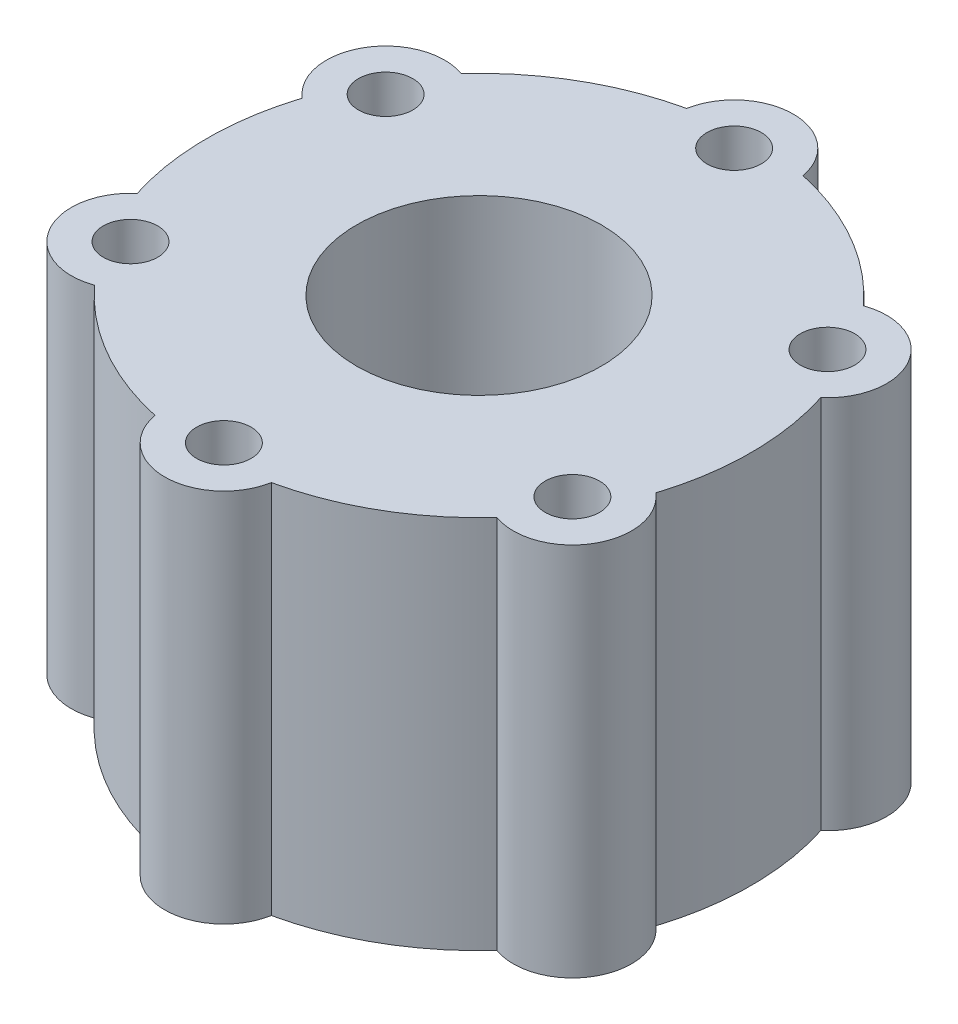
SolidWorks part; units mm, degrees
ref_plane "Front Plane" through (0, 0, 0) normal (0, 0, 1) x (1, 0, 0)
ref_plane "Top Plane" through (0, 0, 0) normal (0, 1, 0) x (1, 0, 0)
ref_plane "Right Plane" through (0, 0, 0) normal (1, 0, 0) x (0, 0, -1)
sketch "Sketch1" plane through (0, 0, 0) normal (0, 1, 0) x (1, 0, 0)
  line L0 (0, 0) -> (0, 23.8125) construction
  line L1 (0, 0) -> (20.6222, 11.9063) construction
  arc A0 (-5.4333, 24.8121) -> (-18.7712, 17.1114) centre (0, 0) ccw
  circle A1 centre (0, 23.8125) radius 2.54
  circle A2 centre (0, 0) radius 29.337 construction
  arc A3 (5.4333, 24.8121) -> (-5.4333, 24.8121) centre (0, 23.8125) ccw
  circle A4 centre (20.6222, 11.9063) radius 2.54
  arc A5 (24.2045, 7.7006) -> (18.7712, 17.1114) centre (20.6222, 11.9063) ccw
  circle A6 centre (20.6222, -11.9062) radius 2.54
  arc A7 (18.7712, -17.1114) -> (24.2045, -7.7006) centre (20.6222, -11.9062) ccw
  circle A8 centre (0, -23.8125) radius 2.54
  arc A9 (-5.4333, -24.8121) -> (5.4333, -24.8121) centre (0, -23.8125) ccw
  circle A10 centre (-20.6222, -11.9063) radius 2.54
  arc A11 (-24.2045, -7.7006) -> (-18.7712, -17.1114) centre (-20.6222, -11.9063) ccw
  circle A12 centre (-20.6222, 11.9062) radius 2.54
  arc A13 (-18.7712, 17.1114) -> (-24.2045, 7.7006) centre (-20.6222, 11.9062) ccw
  arc A14 (-24.2045, 7.7006) -> (-24.2045, -7.7006) centre (0, 0) ccw
  arc A15 (-18.7712, -17.1114) -> (-5.4333, -24.8121) centre (0, 0) ccw
  arc A16 (5.4333, -24.8121) -> (18.7712, -17.1114) centre (0, 0) ccw
  circle A17 centre (0, 0) radius 15.875
  arc A18 (24.2045, -7.7006) -> (24.2045, 7.7006) centre (0, 0) ccw
  arc A19 (18.7712, 17.1114) -> (5.4333, 24.8121) centre (0, 0) ccw
  point P29 (0, 0)
  dimension "D1" = 50.8
  dimension "D2" = 5.08
  dimension "D4" = 58.674
  dimension "D5" = 31.75
  dimension "D3" = 23.8125
  dimension "D6" = 60
extrude "Boss-Extrude1" add sketch "Sketch1" along normal blind 4.699
ref_plane "Plane1" through (0, 35, 0) normal (0, -1, 0) x (-1, 0, 0)
sketch "Sketch2" plane through (0, 4.699, 0) normal (0, 1, 0) x (1, 0, 0)
  circle A0 centre (0, 0) radius 11.426
  circle A1 centre (20.6222, -11.9062) radius 2.54
  circle A2 centre (20.6222, -11.9062) radius 2.54
  circle A3 centre (20.6222, 11.9063) radius 2.54
  circle A4 centre (20.6222, 11.9063) radius 2.54
  circle A5 centre (0, 23.8125) radius 2.54
  circle A6 centre (0, 23.8125) radius 2.54
  circle A7 centre (-20.6222, 11.9062) radius 2.54
  circle A8 centre (-20.6222, 11.9062) radius 2.54
  circle A9 centre (-20.6222, -11.9063) radius 2.54
  circle A10 centre (-20.6222, -11.9063) radius 2.54
  circle A11 centre (0, -23.8125) radius 2.54
  circle A12 centre (0, -23.8125) radius 2.54
  arc A24 (-18.7712, 17.1114) -> (-24.2045, 7.7006) centre (-20.6222, 11.9062) ccw
  arc A25 (-24.2045, 7.7006) -> (-24.2045, -7.7006) centre (0, 0) ccw
  arc A26 (-24.2045, -7.7006) -> (-18.7712, -17.1114) centre (-20.6222, -11.9063) ccw
  arc A27 (-18.7712, -17.1114) -> (-5.4333, -24.8121) centre (0, 0) ccw
  arc A28 (-5.4333, -24.8121) -> (5.4333, -24.8121) centre (0, -23.8125) ccw
  arc A29 (5.4333, -24.8121) -> (18.7712, -17.1114) centre (0, 0) ccw
  arc A30 (18.7712, -17.1114) -> (24.2045, -7.7006) centre (20.6222, -11.9062) ccw
  arc A31 (24.2045, -7.7006) -> (24.2045, 7.7006) centre (0, 0) ccw
  arc A32 (24.2045, 7.7006) -> (18.7712, 17.1114) centre (20.6222, 11.9063) ccw
  arc A33 (18.7712, 17.1114) -> (5.4333, 24.8121) centre (0, 0) ccw
  arc A34 (5.4333, 24.8121) -> (-5.4333, 24.8121) centre (0, 23.8125) ccw
  arc A35 (-5.4333, 24.8121) -> (-18.7712, 17.1114) centre (0, 0) ccw
  arc A36 (-18.7712, 17.1114) -> (-24.2045, 7.7006) centre (-20.6222, 11.9062) ccw
  arc A37 (-24.2045, 7.7006) -> (-24.2045, -7.7006) centre (0, 0) ccw
  arc A38 (-24.2045, -7.7006) -> (-18.7712, -17.1114) centre (-20.6222, -11.9063) ccw
  arc A39 (-18.7712, -17.1114) -> (-5.4333, -24.8121) centre (0, 0) ccw
  arc A40 (-5.4333, -24.8121) -> (5.4333, -24.8121) centre (0, -23.8125) ccw
  arc A41 (5.4333, -24.8121) -> (18.7712, -17.1114) centre (0, 0) ccw
  arc A42 (18.7712, -17.1114) -> (24.2045, -7.7006) centre (20.6222, -11.9062) ccw
  arc A43 (24.2045, -7.7006) -> (24.2045, 7.7006) centre (0, 0) ccw
  arc A44 (24.2045, 7.7006) -> (18.7712, 17.1114) centre (20.6222, 11.9063) ccw
  arc A45 (18.7712, 17.1114) -> (5.4333, 24.8121) centre (0, 0) ccw
  arc A46 (5.4333, 24.8121) -> (-5.4333, 24.8121) centre (0, 23.8125) ccw
  arc A47 (-5.4333, 24.8121) -> (-18.7712, 17.1114) centre (0, 0) ccw
  dimension "D8" = 22.852
  dimension "D1" = 0
  dimension "D2" = 0
  dimension "D3" = 0
  dimension "D4" = 0
  dimension "D5" = 0
  dimension "D6" = 0
  dimension "D7" = 0
extrude "Boss-Extrude2" add sketch "Sketch2" along normal up to surface (30.301 mm away) up to plane "Plane1"
ref_axis "Axis1" through (0, -0.2631, 0) along (0, 1, 0)
sketch "Sketch3" plane through (0, 0, 0) normal (0, 0, 1) x (1, 0, 0)
  line L0 (11.426, 4.699) -> (18.415, 2.0748) construction
  line L1 (-15.875, 4.699) -> (15.875, 4.699) construction
  line L2 (-11.426, 4.699) -> (11.426, 4.699) construction
  line L3 (18.415, 2.0748) -> (18.415, 4.699)
  line L4 (18.415, 4.699) -> (11.426, 4.699)
  line L5 (18.415, 2.0748) -> (18.415, 0) construction
  line L6 (5.4333, 0) -> (18.7712, 0) construction
  line L7 (18.415, 2.0748) -> (15.875, 2.0748)
  line L8 (15.875, 2.0748) -> (11.426, 4.699)
  line L9 (15.875, 2.0748) -> (15.875, 4.699) construction
  point P6 (0, 0)
  point P12 (16.1073, 2.0748)
  dimension "D1" = 2.0748
  dimension "D2" = 2.54
revolve "Revolve1" add sketch "Sketch3" angle 360 about axis through (0, -0.2631, 0) along (0, 1, 0)
